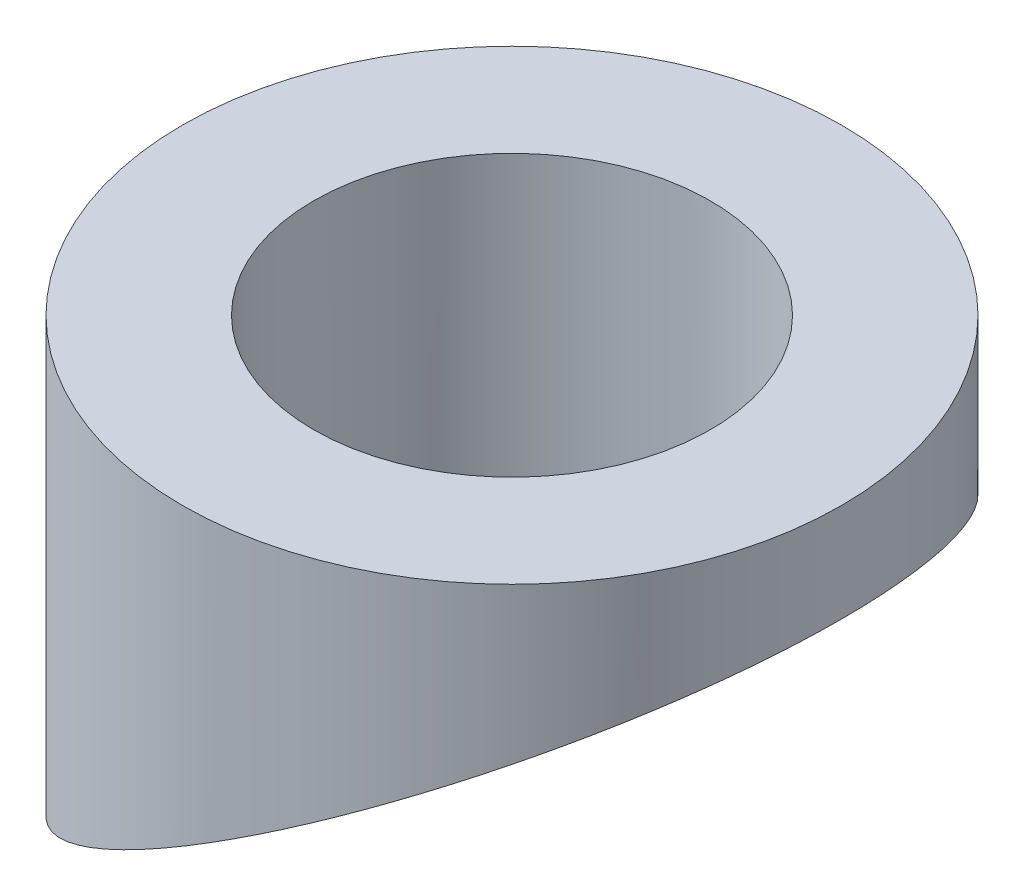
SolidWorks part; units mm, degrees
ref_plane "Front Plane" through (0, 0, 0) normal (0, 0, 1) x (1, 0, 0)
ref_plane "Top Plane" through (0, 0, 0) normal (0, 1, 0) x (1, 0, 0)
ref_plane "Right Plane" through (0, 0, 0) normal (1, 0, 0) x (0, 0, -1)
sketch "Sketch1" plane through (0, 0, 0) normal (0, 1, 0) x (1, 0, 0)
  circle A0 centre (0, 0) radius 6.05
  circle A1 centre (0, 0) radius 10.05
  dimension "D1" = 12.1
  dimension "D2" = 4
extrude "Boss-Extrude1" add sketch "Sketch1" along normal blind 15
sketch "Sketch3" plane through (0, 0, 0) normal (0, 0, 1) x (1, 0, 0)
  line L0 (-10.05, 0) -> (10.05, 12)
  line L1 (10.05, 0) -> (10.05, 15) construction
  line L2 (10.05, 12) -> (10.05, 0)
  line L3 (10.05, 0) -> (-10.05, 0)
  dimension "D1" = 12
extrude "Cut-Extrude1" cut sketch "Sketch3" against normal mid plane 30
